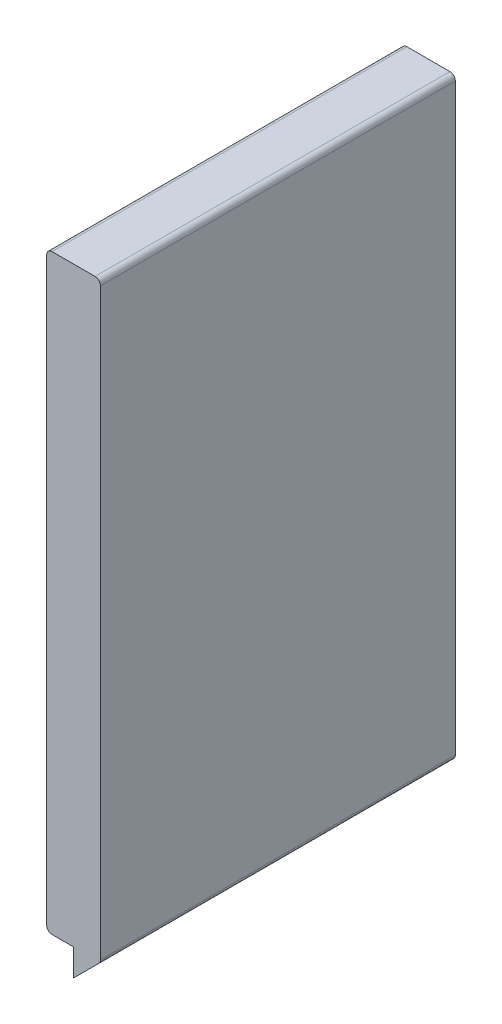
SolidWorks part; units mm, degrees
ref_plane "Front Plane" through (0, 0, 0) normal (0, 0, 1) x (1, 0, 0)
ref_plane "Top Plane" through (0, 0, 0) normal (0, 1, 0) x (1, 0, 0)
ref_plane "Right Plane" through (0, 0, 0) normal (1, 0, 0) x (0, 0, -1)
sketch "Sketch1" plane through (0, 0, 0) normal (0, 0, 1) x (1, 0, 0)
  line L1 (5, -55) -> (5, -60)
  line L2 (5, -60) -> (10, -55)
  line L3 (0, 55) -> (0, -55)
  line L4 (0, -55) -> (5, -55)
  line L5 (10, -55) -> (10, 55)
  line L6 (10, 55) -> (0, 55)
  point P6 (0, 0)
  point P7 (0, 0)
  point P9 (0, 0)
  dimension "D1" = 5
  dimension "D2" = 10
  dimension "D3" = 5
  dimension "D4" = 110
extrude "Boss-Extrude1" add sketch "Sketch1" along normal mid plane 66
fillet "Fillet1" radius 1 4 edges at (0, 55, 0) (0, -55, 0) (10, 55, 0) (10, -55, 0)
